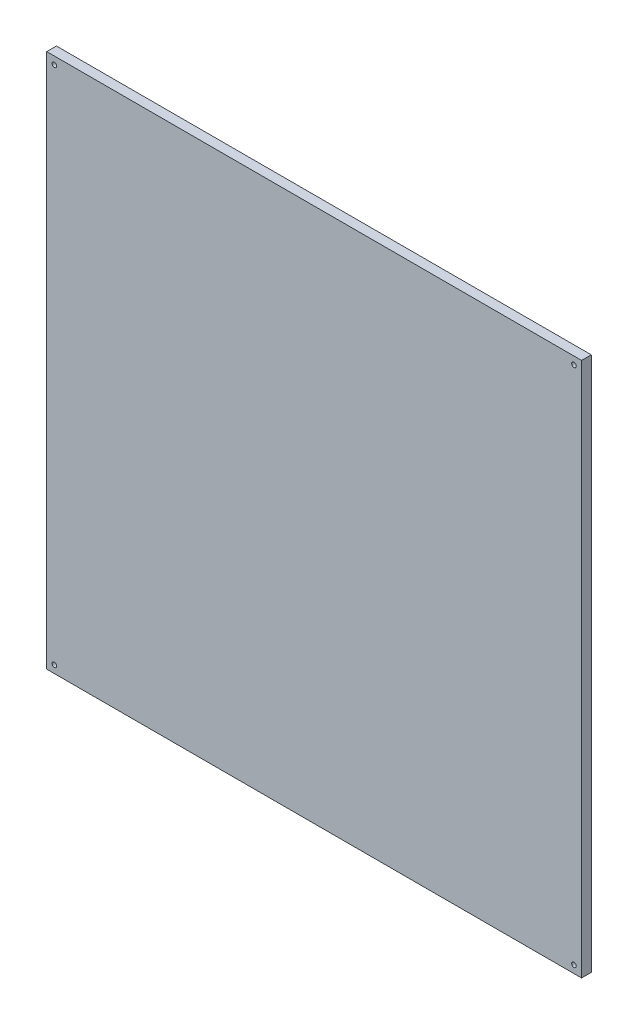
SolidWorks part; units mm, degrees
ref_plane "Front Plane" through (0, 0, 0) normal (0, 0, 1) x (1, 0, 0)
ref_plane "Top Plane" through (0, 0, 0) normal (0, 1, 0) x (1, 0, 0)
ref_plane "Right Plane" through (0, 0, 0) normal (1, 0, 0) x (0, 0, -1)
sketch "Sketch1" plane through (0, 0, 0) normal (0, 0, 1) x (1, 0, 0)
  line L1 (0, 0) -> (350, 0)
  line L2 (0, 0) -> (0, 350)
  line L3 (0, 350) -> (350, 350)
  line L4 (350, 0) -> (350, 350)
  dimension "D1" = 350
  dimension "D2" = 350
extrude "Boss-Extrude1" add sketch "Sketch1" along normal blind 6.35
sketch "Sketch2" plane through (0, 0, 6.35) normal (0, 0, 1) x (1, 0, 0)
  line L0 (350, 350) -> (0, 350) construction
  line L1 (0, 350) -> (0, 0) construction
  circle A1 centre (5, 345) radius 1.5
  point P6 (0, 0)
  dimension "D1" = 5
  dimension "D2" = 5
extrude "Cut-Extrude1" cut sketch "Sketch2" against normal blind 10
pattern_circular "CirPattern1" count 4 over 360 about axis through (175.0098, 174.9902, 0) along (0, 0, 1) of "Cut-Extrude1"
